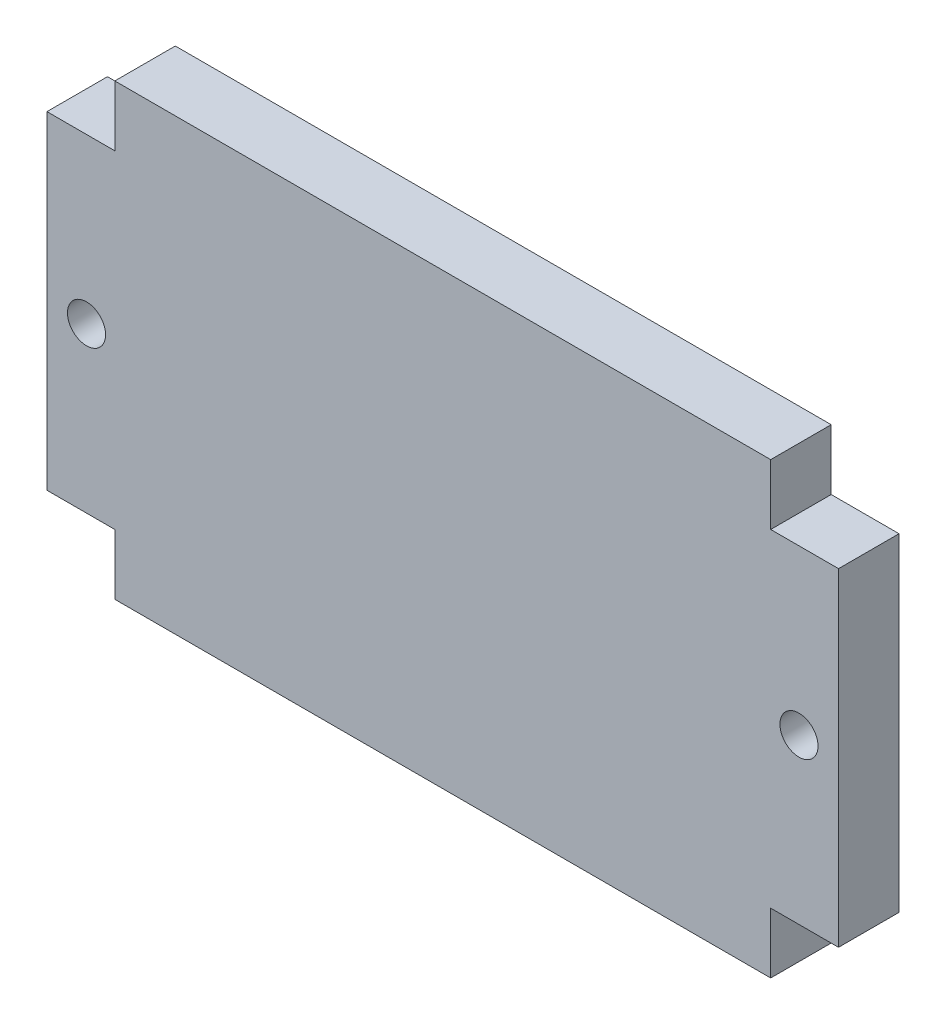
SolidWorks part; units mm, degrees
ref_plane "Front Plane" through (0, 0, 0) normal (0, 0, 1) x (1, 0, 0)
ref_plane "Top Plane" through (0, 0, 0) normal (0, 1, 0) x (1, 0, 0)
ref_plane "Right Plane" through (0, 0, 0) normal (1, 0, 0) x (0, 0, -1)
sketch "Model" plane through (0, 0, 0) normal (0, 0, 1) x (1, 0, 0)
  line L0 (0, 0) -> (0, 39.7) construction
  line L1 (-29, 0) -> (29, 0)
  line L2 (-29, 0) -> (-29, 5.35)
  line L3 (-29, 39.7) -> (29, 39.7)
  line L4 (29, 0) -> (29, 5.35)
  line L5 (-29, 34.35) -> (-35, 34.35)
  line L6 (35, 34.35) -> (35, 5.35)
  line L7 (-29, 5.35) -> (-35, 5.35)
  line L8 (-35, 34.35) -> (-35, 5.35)
  line L9 (-29, 34.35) -> (-29, 39.7)
  line L10 (29, 5.35) -> (35, 5.35)
  line L11 (29, 34.35) -> (35, 34.35)
  line L12 (29, 34.35) -> (29, 39.7)
  line L13 (-35, 19.85) -> (35, 19.85) construction
  circle A0 centre (-31.5, 19.85) radius 1.685
  circle A1 centre (31.5, 19.85) radius 1.685
  dimension "D8" = 3.37
  dimension "D2" = 39.7
  dimension "D5" = 6
  dimension "D6" = 5.35
  dimension "D10" = 3.5
  dimension "D11" = 70
extrude "Boss-Extrude1" add sketch "Model" along normal blind 5.35
equation "\"mdfthick\"=5.35"
equation "\"D6@Model\"=\"mdfthick\""
equation "\"D1@Boss-Extrude1\"=\"mdfthick\""
